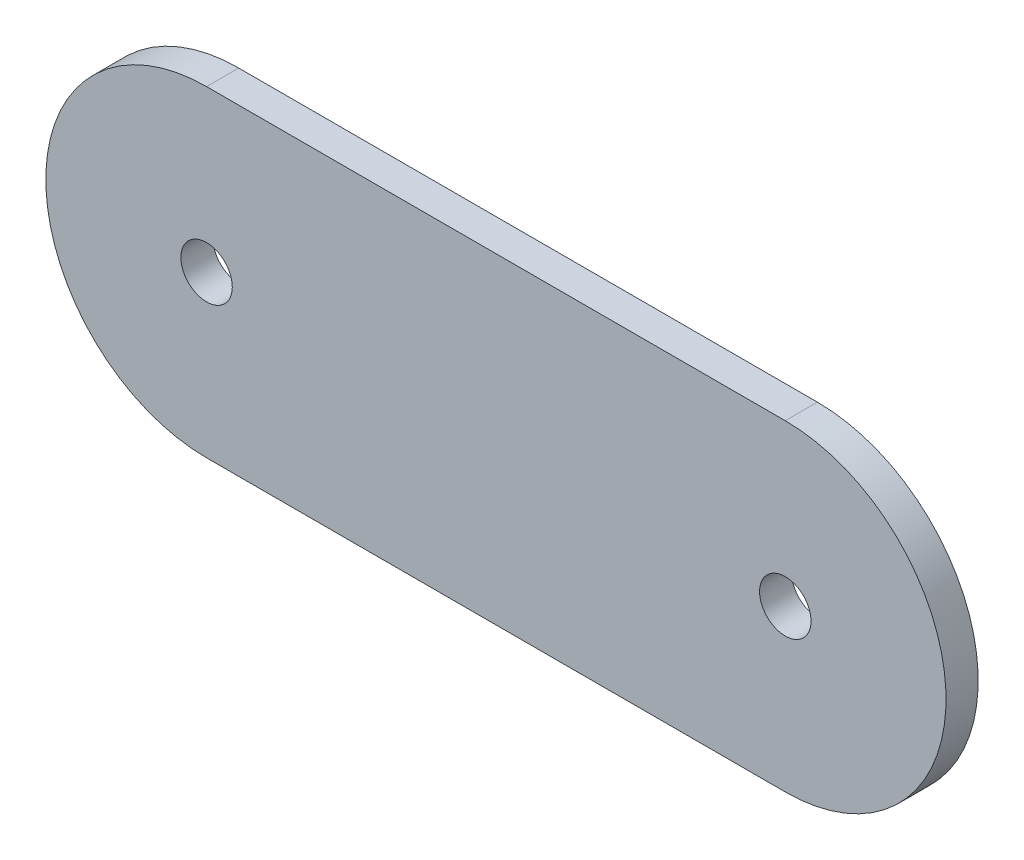
SolidWorks part; units mm, degrees
material "Custom Plastic"
ref_plane "Alzado" through (0, 0, 0) normal (0, 0, 1) x (1, 0, 0)
ref_plane "Planta" through (0, 0, 0) normal (0, 1, 0) x (1, 0, 0)
ref_plane "Vista lateral" through (0, 0, 0) normal (1, 0, 0) x (0, 0, -1)
sketch "Sketch1" plane through (0, 0, 0) normal (0, 0, 1) x (1, 0, 0)
  line L0 (-29.1999, 0) -> (15.8001, 0) construction
  line L1 (-29.1999, 12.5) -> (15.8001, 12.5)
  line L2 (-29.1999, -12.5) -> (15.8001, -12.5)
  arc A0 (-29.1999, 12.5) -> (-29.1999, -12.5) centre (-29.1999, 0) ccw
  arc A1 (15.8001, -12.5) -> (15.8001, 12.5) centre (15.8001, 0) ccw
  circle A2 centre (-29.1999, 0) radius 2
  circle A3 centre (15.8001, 0) radius 2
  point P3 (-6.6999, 0)
  point P8 (-41.6999, 0)
  point P9 (28.3001, 0)
  dimension "D2" = 4
  dimension "D3" = 4
  dimension "D1" = 70
  dimension "D4" = 25
extrude "Boss-Extrude1" add sketch "Sketch1" along normal blind 2.5
